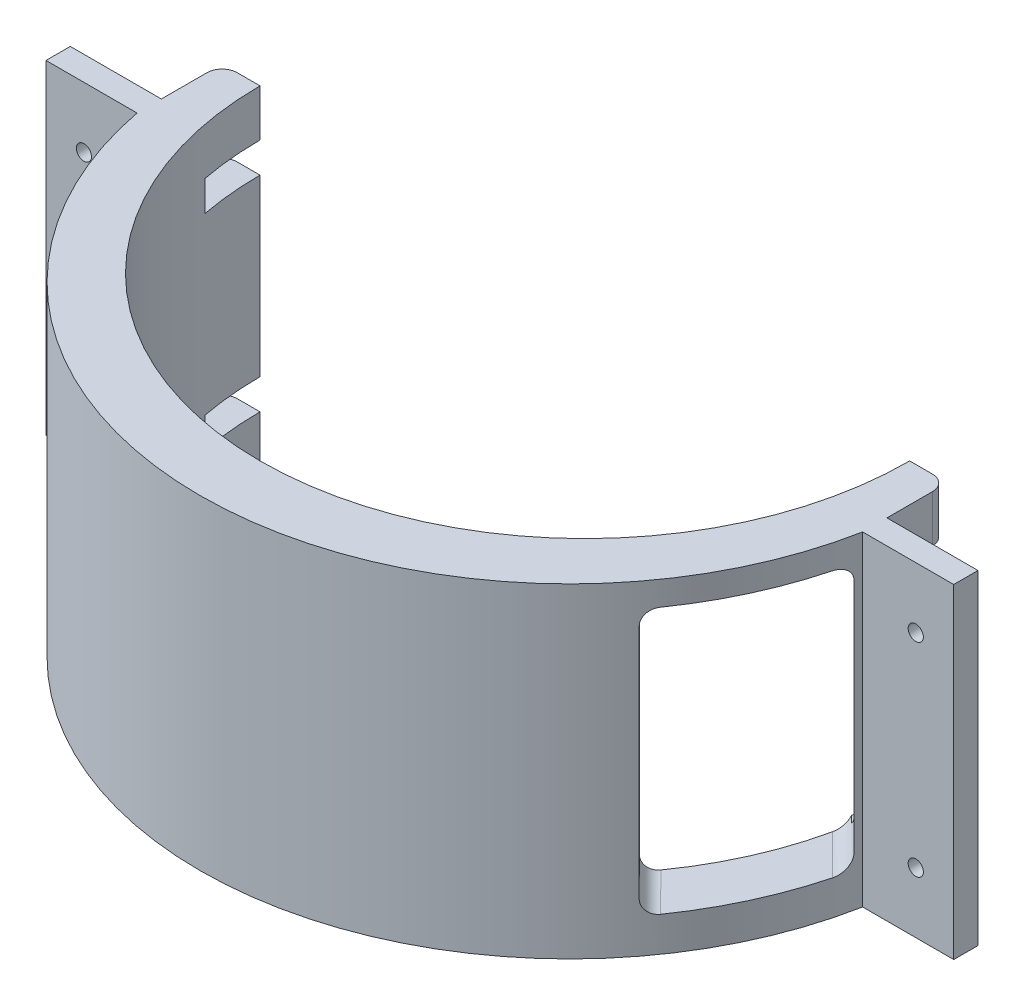
SolidWorks part; units mm, degrees
ref_plane "Front Plane" through (0, 0, 0) normal (0, 0, 1) x (1, 0, 0)
ref_plane "Top Plane" through (0, 0, 0) normal (0, 1, 0) x (1, 0, 0)
ref_plane "Right Plane" through (0, 0, 0) normal (1, 0, 0) x (0, 0, -1)
sketch "Sketch1" plane through (0, 0, 0) normal (0, 1, 0) x (1, 0, 0)
  line L0 (0, 0) -> (0, -8)
  line L1 (0, -8) -> (30, -8)
  line L2 (0, 0) -> (30, 0)
  line L3 (30, 0) -> (30, 15)
  line L4 (35, 20) -> (42.5, 20)
  line L5 (269, -8) -> (299, -8)
  line L6 (299, -8) -> (299, 0)
  line L7 (299, 0) -> (269, 0)
  line L8 (269, 0) -> (269, 15)
  line L9 (264, 20) -> (256.5, 20)
  arc A0 (30, -8) -> (269, -8) centre (149.5, 14.9181) ccw
  arc A1 (42.5, 20) -> (256.5, 20) centre (149.5, 20) ccw
  arc A2 (269, 15) -> (264, 20) centre (264, 15) ccw
  arc A3 (30, 15) -> (35, 20) centre (35, 15) cw
  dimension "D1" = 107
  dimension "D2" = 30
  dimension "D3" = 5
  dimension "D9" = 8
  dimension "D4" = 12.5
  dimension "D5" = 12.5
  dimension "D6" = 20
  dimension "D7" = 20
  dimension "D8" = 214
  dimension "D10" = 30
extrude "Boss-Extrude1" add sketch "Sketch1" along normal blind 107
sketch "Sketch2" plane through (0, 0, 0) normal (0, 0, -1) x (-1, 0, 0)
  line L1 (-269, 107) -> (-299, 107) construction
  line L2 (0, 0) -> (-30, 0) construction
  line L3 (-269, 0) -> (-299, 0) construction
  line L5 (-299, 107) -> (-299, 0) construction
  line L6 (-30, 107) -> (0, 107) construction
  circle A0 centre (-286.5, 87) radius 2.5
  circle A1 centre (-286.5, 20) radius 2.5
  circle A2 centre (-12.5, 87) radius 2.5
  circle A3 centre (-12.5, 20) radius 2.5
  dimension "D1" = 5
  dimension "D2" = 274
  dimension "D3" = 20
  dimension "D4" = 20
  dimension "D5" = 20
  dimension "D6" = 20
  dimension "D8" = 12.5
extrude "Cut-Extrude1" cut sketch "Sketch2" against normal through all
ref_plane "Plane1" through (152.699, 0, 153.5193) normal (0.7052, 0, 0.709) x (0.709, 0, -0.7052)
sketch "Sketch3" plane through (152.699, 0, 153.5193) normal (0.7052, 0, 0.709) x (0.709, 0, -0.7052)
  circle A0 centre (109.1096, 56.8658) radius 35
  dimension "D1" = 70
extrude "Cut-Extrude2" [suppressed] cut sketch "Sketch3" against normal blind 10 contours A0
sketch "Sketch4" [suppressed] plane through (145.6469, 0, 146.4293) normal (0.7052, 0, 0.709) x (0.709, 0, -0.7052)
  circle A0 centre (109.1096, 56.8658) radius 31.7783
extrude "Cut-Extrude3" [suppressed] cut sketch "Sketch4" against normal blind 25
sketch "Sketch5" plane through (0, 0, 0) normal (0, 0, -1) x (-1, 0, 0)
  line L1 (-269, 91.5355) -> (-253.4572, 91.5355)
  line L2 (-269, 91.5355) -> (-269, 81.5355)
  line L3 (-269, 81.5355) -> (-253.4572, 81.5355)
  line L4 (-253.4572, 91.5355) -> (-253.4572, 81.5355)
  line L5 (-269, 91.5355) -> (-253.4572, 81.5355) construction
  line L6 (-269, 81.5355) -> (-253.4572, 91.5355) construction
  line L7 (-269, 107) -> (-269, 0) construction
  line L8 (-269, 24.0087) -> (-250.3633, 24.0087)
  line L9 (-269, 24.0087) -> (-269, 14.0087)
  line L10 (-269, 14.0087) -> (-250.3633, 14.0087)
  line L11 (-250.3633, 24.0087) -> (-250.3633, 14.0087)
  line L12 (-269, 24.0087) -> (-250.3633, 14.0087) construction
  line L13 (-269, 14.0087) -> (-250.3633, 24.0087) construction
  line L14 (-149.5, 107) -> (-149.5, -6.1921) construction
  line L15 (-42.5, 107) -> (-256.5, 107) construction
  line L16 (-30, 81.5355) -> (-45.5428, 91.5355) construction
  line L17 (-30, 91.5355) -> (-45.5428, 81.5355) construction
  line L18 (-30, 14.0087) -> (-48.6367, 24.0087) construction
  line L19 (-30, 24.0087) -> (-48.6367, 14.0087) construction
  line L20 (-48.6367, 24.0087) -> (-48.6367, 14.0087)
  line L21 (-30, 14.0087) -> (-48.6367, 14.0087)
  line L22 (-30, 24.0087) -> (-30, 14.0087)
  line L23 (-30, 24.0087) -> (-48.6367, 24.0087)
  line L24 (-45.5428, 91.5355) -> (-45.5428, 81.5355)
  line L25 (-30, 91.5355) -> (-30, 81.5355)
  line L26 (-30, 91.5355) -> (-45.5428, 91.5355)
  line L27 (-30, 81.5355) -> (-45.5428, 81.5355)
  point P0 (-261.2286, 86.5355)
  point P7 (-259.6816, 19.0087)
  point P22 (-37.7714, 86.5355)
  point P27 (-39.3184, 19.0087)
  dimension "D1" = 67.5445
  dimension "D2" = 10
  dimension "D3" = 10
extrude "Cut-Extrude4" cut sketch "Sketch5" along normal up to surface (20 mm away) up to face at (260.25, 53.5, -20)
sketch "Sketch6" plane through (152.699, 0, 153.5193) normal (0.7052, 0, 0.709) x (0.709, 0, -0.7052)
  line L0 (120.7029, 126.4256) -> (120.7029, -33.6368) construction
ref_plane "Plane3" through (0, 0, 30) normal (0, 0, 1) x (1, 0, 0)
sketch "Sketch8" plane through (152.699, 0, 153.5193) normal (0.7052, 0, 0.709) x (0.709, 0, -0.7052)
  line L0 (185.0789, 107) -> (185.0789, 0) construction
  line L1 (138.0789, 99.0219) -> (178.0789, 99.0219)
  line L2 (133.0789, 94.0219) -> (133.0789, 16.4375)
  line L3 (138.0789, 11.4375) -> (178.0789, 11.4375)
  line L4 (183.0789, 94.0219) -> (183.0789, 16.4375)
  arc A0 (178.0789, 11.4375) -> (183.0789, 16.4375) centre (178.0789, 16.4375) ccw
  arc A1 (133.0789, 16.4375) -> (138.0789, 11.4375) centre (138.0789, 16.4375) ccw
  arc A2 (178.0789, 99.0219) -> (183.0789, 94.0219) centre (178.0789, 94.0219) cw
  arc A3 (138.0789, 99.0219) -> (133.0789, 94.0219) centre (138.0789, 94.0219) ccw
  dimension "D3" = 5
  dimension "D1" = 50
  dimension "D2" = 2
extrude "Cut-Extrude5" cut sketch "Sketch8" against normal through all and the other way through all
